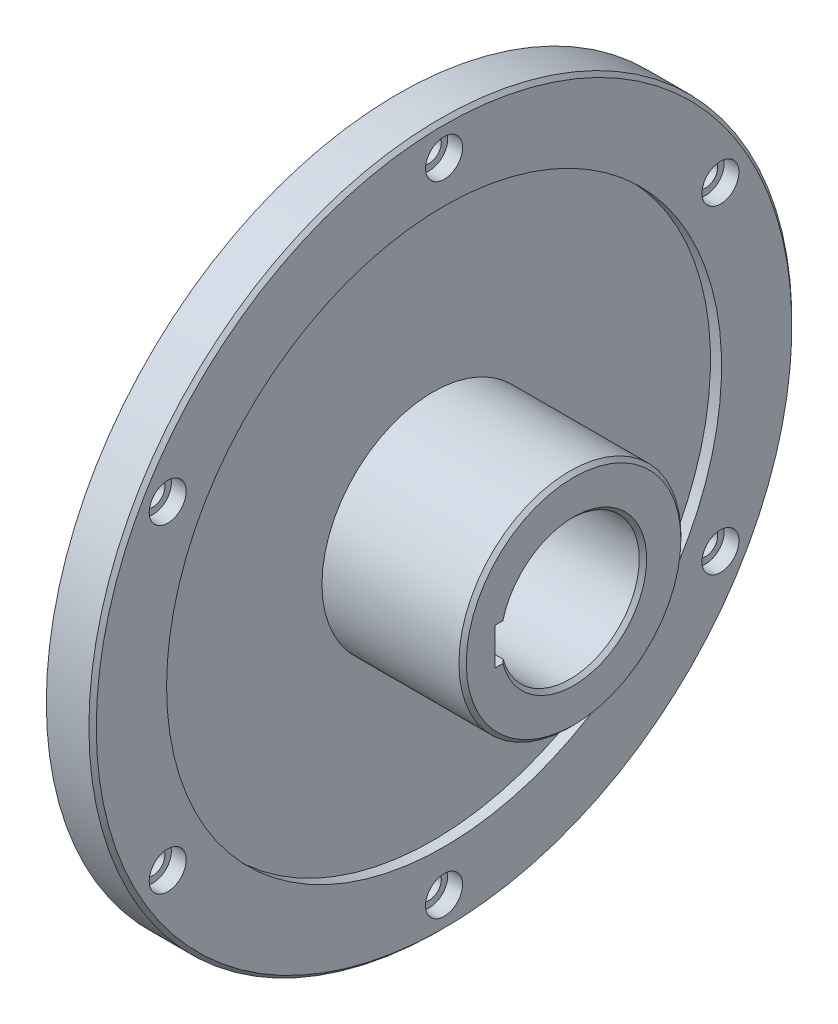
SolidWorks part; units mm, degrees
ref_plane "Спереди" through (0, 0, 0) normal (0, 0, 1) x (1, 0, 0)
ref_plane "Сверху" through (0, 0, 0) normal (0, 1, 0) x (1, 0, 0)
ref_plane "Справа" through (0, 0, 0) normal (1, 0, 0) x (0, 0, -1)
sketch "Эскиз1" plane through (0, 0, 0) normal (0, 0, 1) x (1, 0, 0)
  line L1 (-18.0393, 135) -> (-18.0393, 150)
  line L2 (-18.0393, 150) -> (-13.0393, 150)
  line L3 (-13.0393, 150) -> (-13.0393, 190)
  line L4 (-13.0393, 190) -> (11.9607, 190)
  line L5 (11.9607, 190) -> (11.9607, 150)
  line L7 (81.9607, 60) -> (81.9607, 37.5)
  line L8 (11.9607, 150) -> (5.9607, 150)
  line L9 (5.9607, 150) -> (5.9607, 60)
  line L11 (-18.0393, 135) -> (-12.0393, 135)
  line L12 (-12.0393, 135) -> (-12.0393, 60)
  line L13 (5.9607, 60) -> (81.9607, 60)
  line L14 (-12.0393, 60) -> (-18.0393, 60)
  line L15 (-18.0393, 60) -> (-18.0393, 37.5)
  line L16 (-18.0393, 37.5) -> (81.9607, 37.5)
  line L17 (-127.4203, 0) -> (207.2223, 0) construction
  dimension "D1" = 75
  dimension "D2" = 120
  dimension "D3" = 380
  dimension "D4" = 300
  dimension "D5" = 300
  dimension "D6" = 100
  dimension "D7" = 25
  dimension "D8" = 5
  dimension "D9" = 6
  dimension "D10" = 6
  dimension "D11" = 270
revolve "Повернуть1" add sketch "Эскиз1" angle 360 about L17
sketch "Эскиз3" plane through (0, 0, 0) normal (1, 0, 0) x (0, 0, -1)
  line L0 (0, 93.6106) -> (0, -97.0765) construction
  line L1 (-42.4, 10) -> (-42.4, -10)
  line L2 (-42.4, -10) -> (0, -10)
  line L3 (0, -10) -> (0, 10)
  line L4 (0, 10) -> (-42.4, 10)
  line L5 (-202.3794, 0) -> (239.1876, 0) construction
  line L6 (37.5, 0) -> (37.5, 65.1224) construction
  circle A0 centre (0, 0) radius 37.5 construction
  dimension "D1" = 20
  dimension "D2" = 79.9
extrude "Вырез-Вытянуть1" cut sketch "Эскиз3" against normal through all both and the other way through all
sketch "Эскиз4" plane through (0, 0, 0) normal (1, 0, 0) x (0, 0, -1)
  line L0 (0, 214.2355) -> (0, -239.2017) construction
  circle A0 centre (0, 0) radius 172.5 construction
  circle A1 centre (0, -172.5) radius 10
  dimension "D1" = 345
  dimension "D2" = 20
extrude "Вырез-Вытянуть2" cut sketch "Эскиз4" against normal blind 8 from surface
sketch "Эскиз5" plane through (3.9607, 0, 0) normal (1, 0, 0) x (0, 0, -1)
  circle A0 centre (0, -172.5) radius 6.5
  dimension "D1" = 13
extrude "Вырез-Вытянуть3" cut sketch "Эскиз5" against normal through all
pattern_circular "Круговой массив1" count 6 over 360 about axis through (0, 0, 0) along (1, 0, 0) of "Вырез-Вытянуть3", "Вырез-Вытянуть2"
chamfer "Фаска1" distance 2 angle 45 6 edges at (81.9607, 0, 60) (-18.0393, 0, -37.5) (-18.0393, 0, 150) (-18.0393, 0, 60) (81.9607, 0, -37.5) (11.9607, 0, 190)
